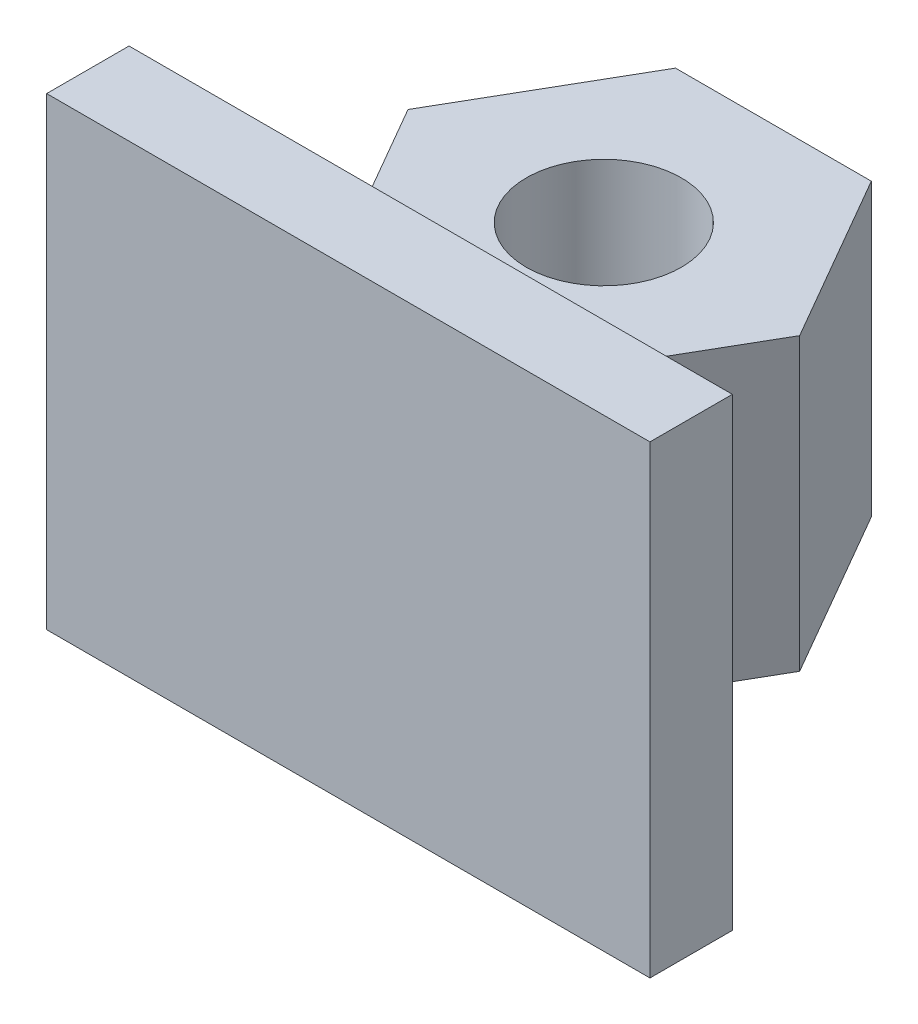
SolidWorks part; units mm, degrees
ref_plane "Alzado" through (0, 0, 0) normal (0, 0, 1) x (1, 0, 0)
ref_plane "Planta" through (0, 0, 0) normal (0, 1, 0) x (1, 0, 0)
ref_plane "Vista lateral" through (0, 0, 0) normal (1, 0, 0) x (0, 0, -1)
sketch "Croquis1" plane through (0, 0, 0) normal (0, 1, 0) x (1, 0, 0)
  line L1 (20.2073, 0) -> (10.1036, 17.5)
  line L2 (10.1036, 17.5) -> (-10.1036, 17.5)
  line L3 (-10.1036, 17.5) -> (-20.2073, 0)
  line L4 (-20.2073, 0) -> (-10.1036, -17.5)
  line L5 (-10.1036, -17.5) -> (10.1036, -17.5)
  line L6 (10.1036, -17.5) -> (20.2073, 0)
  circle A0 centre (0, 0) radius 8
  circle A1 centre (0, 0) radius 17.5 construction
  dimension "D1" = 16
  dimension "D2" = 35
extrude "Saliente-Extruir1" add sketch "Croquis1" along normal blind 30
sketch "Croquis2" plane through (0, 0, 17.5) normal (0, 0, 1) x (1, 0, 0)
  line L1 (-31.4935, 38.7809) -> (30.7602, 38.7809)
  line L2 (-31.4935, 38.7809) -> (-31.4935, -9.1293)
  line L3 (-31.4935, -9.1293) -> (30.7602, -9.1293)
  line L4 (30.7602, 38.7809) -> (30.7602, -9.1293)
extrude "Saliente-Extruir2" add sketch "Croquis2" along normal blind 8.5
